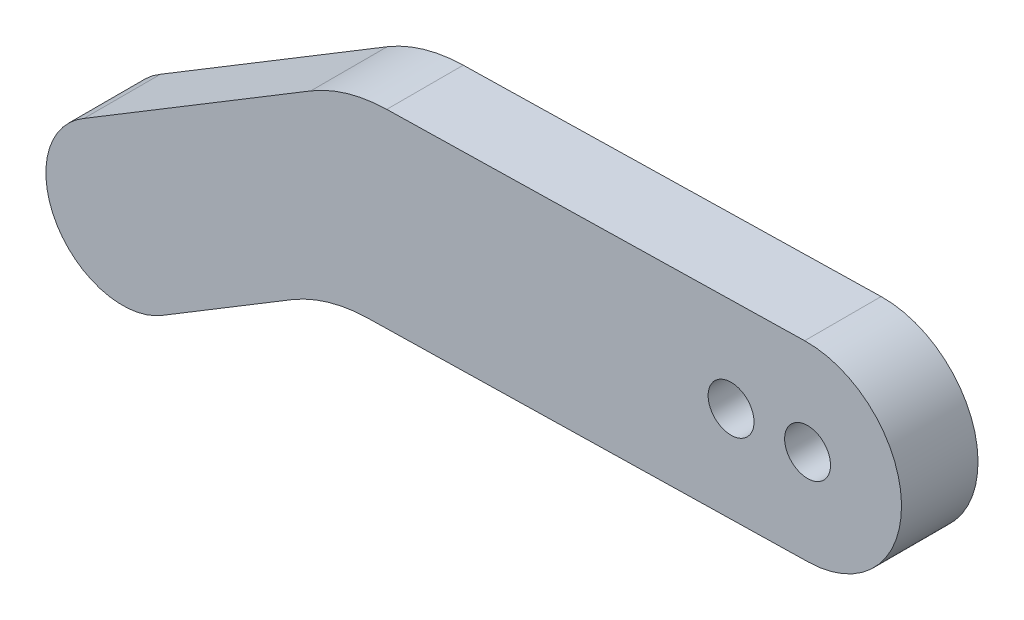
SolidWorks part; units mm, degrees
ref_plane "Front Plane" through (0, 0, 0) normal (0, 0, 1) x (1, 0, 0)
ref_plane "Top Plane" through (0, 0, 0) normal (0, 1, 0) x (1, 0, 0)
ref_plane "Right Plane" through (0, 0, 0) normal (1, 0, 0) x (0, 0, -1)
sketch "Sketch3" plane through (0, 0, 0) normal (0, 0, 1) x (1, 0, 0)
  line L0 (0, 0) -> (14.8191, 8.9662)
  line L1 (0, 0) -> (5.1766, -8.5558) construction
  line L2 (5.1766, -8.5558) -> (13.5789, -3.4721)
  line L3 (19.7906, 10.4083) -> (47.1054, 10.9688)
  line L4 (47.1054, 10.9688) -> (47.36, -1.4388) construction
  line L5 (18.5504, -2.0301) -> (47.36, -1.4388)
  arc A0 (47.1054, 10.9688) -> (47.36, -1.4388) centre (47.2327, 4.765) cw
  arc A1 (0, 0) -> (5.1766, -8.5558) centre (2.5115, -4.3244) ccw
  arc A2 (14.8191, 8.9662) -> (19.7906, 10.4083) centre (19.9958, 0.4104) cw
  arc A3 (13.5789, -3.4721) -> (18.5504, -2.0301) centre (18.7556, -12.028) cw
  point P10 (17.1117, 10.3533)
  point P13 (19.9017, -5.697)
  point P15 (15.8714, -2.085)
  dimension "D7" = 5.0008
  dimension "D8" = 10
  dimension "D9" = 10
  dimension "D1" = 20
  dimension "D2" = 30
  dimension "D3" = 150
  dimension "D4" = 31.4886
  dimension "D5" = 12.5
  dimension "D6" = 10
extrude "Boss-Extrude1" add sketch "Sketch3" along normal blind 5 contours L0 A1 L2 L5 A0 L3
sketch "Sketch4" plane through (0, 0, 5) normal (0, 0, 1) x (1, 0, 0)
  line L0 (47.2327, 10.9701) -> (47.36, -1.4388) construction
  line L1 (47.2963, 4.7657) -> (21.304, 4.499) construction
  circle A0 centre (47.2963, 4.7657) radius 1.5
  arc A1 (47.36, -1.4388) -> (47.1054, 10.9688) centre (47.2327, 4.765) ccw construction
  circle A2 centre (42.2963, 4.7144) radius 1.5
  point P9 (47.2963, 4.7657)
  dimension "D1" = 3
  dimension "D2" = 5
  dimension "D3" = 3
extrude "Cut-Extrude1" cut sketch "Sketch4" against normal blind 7
